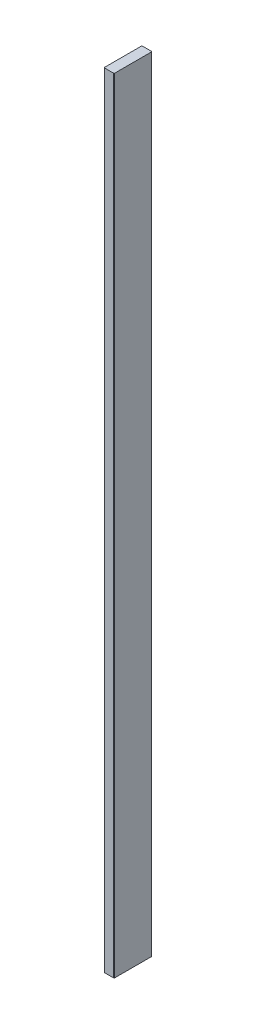
SolidWorks part; units mm, degrees
ref_plane "Front Plane" through (0, 0, 0) normal (0, 0, 1) x (1, 0, 0)
ref_plane "Top Plane" through (0, 0, 0) normal (0, 1, 0) x (1, 0, 0)
ref_plane "Right Plane" through (0, 0, 0) normal (1, 0, 0) x (0, 0, -1)
sketch "Sketch1" plane through (0, 0, 0) normal (0, 1, 0) x (1, 0, 0)
  line L1 (-16, -60) -> (16, -60)
  line L2 (-16, -60) -> (-16, 60)
  line L3 (-16, 60) -> (16, 60)
  line L4 (16, -60) -> (16, 60)
  line L5 (-16, -60) -> (16, 60) construction
  line L6 (-16, 60) -> (16, -60) construction
  point P0 (0, 0)
  dimension "D1" = 32
  dimension "D2" = 120
extrude "Boss-Extrude1" add sketch "Sketch1" along normal blind 2482
fillet "Fillet1" radius 2 4 edges at (-16, 1241, -60) (16, 1241, -60) (-16, 1241, 60) (16, 1241, 60)
sketch "Sketch2" plane through (0, 0, 0) normal (0, -1, 0) x (1, 0, 0)
  circle A0 centre (0, 0) radius 6
  dimension "D1" = 12
extrude "Cut-Extrude1" cut sketch "Sketch2" against normal blind 30
